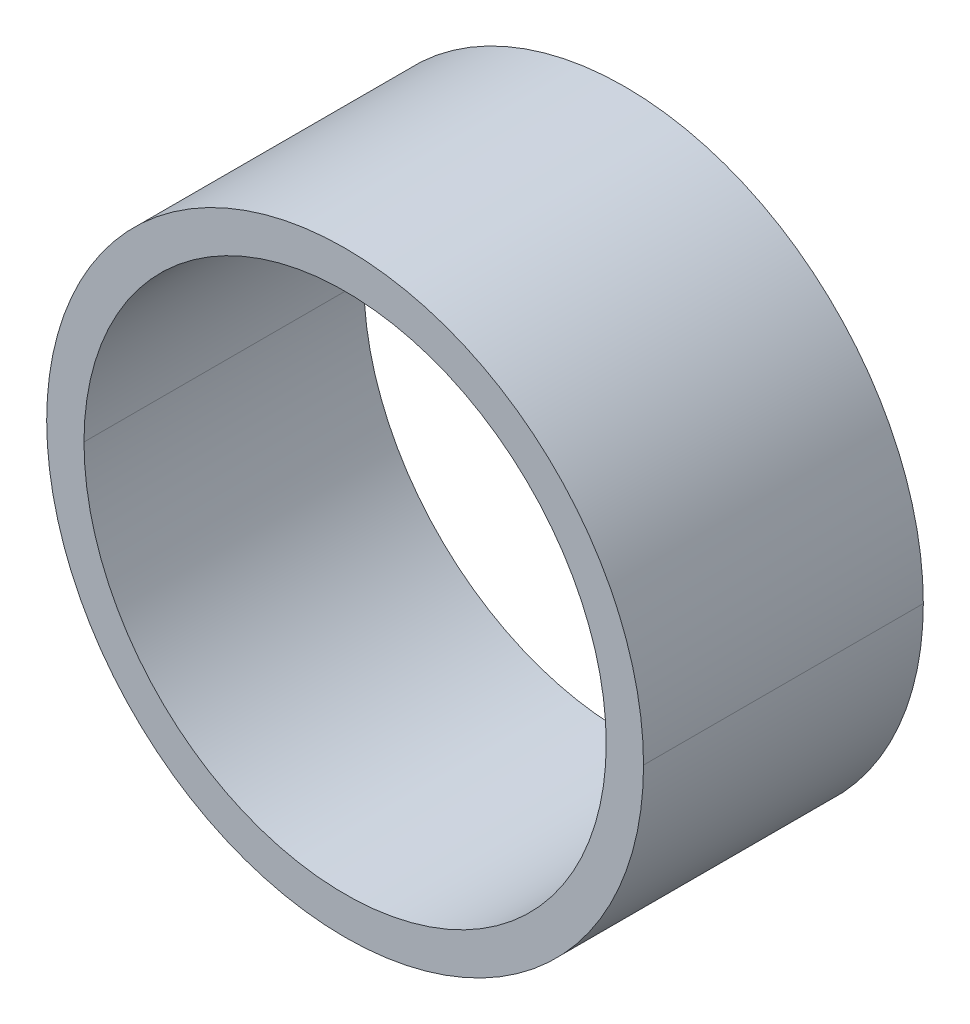
SolidWorks part; units mm, degrees
ref_plane "Front Plane" through (0, 0, 0) normal (0, 0, 1) x (1, 0, 0)
ref_plane "Top Plane" through (0, 0, 0) normal (0, 1, 0) x (1, 0, 0)
ref_plane "Right Plane" through (0, 0, 0) normal (1, 0, 0) x (0, 0, -1)
other "Configuration Table"
sketch "Sketch1" plane through (0, 0, 0) normal (0, 0, 1) x (1, 0, 0)
  circle A0 centre (0, 0) radius 17.78
  circle A1 centre (0, 0) radius 20.32
  dimension "D1" = 35.56
  dimension "D2" = 40.64
extrude "Extrude1" add sketch "Sketch1" along normal blind 19.05
split line "Split Line1"
